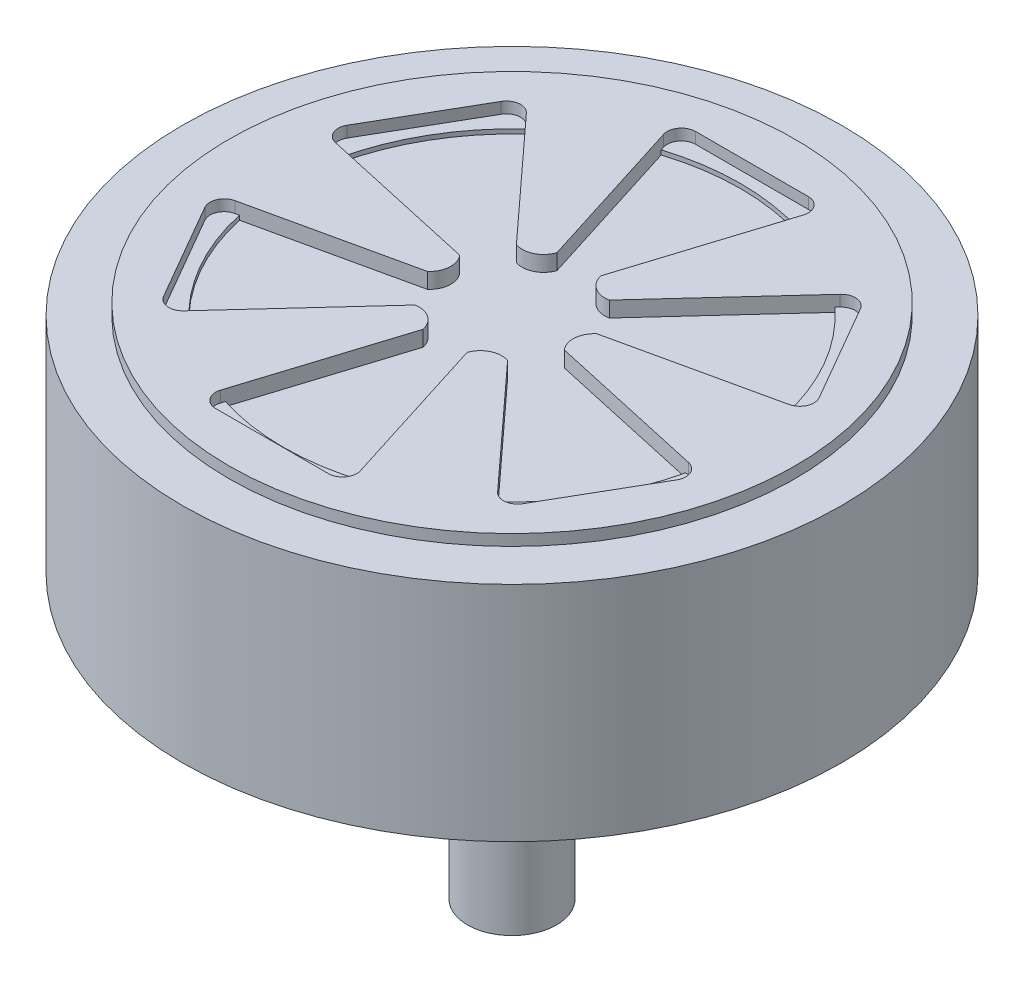
SolidWorks part; units mm, degrees
ref_plane "Front Plane" through (0, 0, 0) normal (0, 0, 1) x (1, 0, 0)
ref_plane "Top Plane" through (0, 0, 0) normal (0, 1, 0) x (1, 0, 0)
ref_plane "Right Plane" through (0, 0, 0) normal (1, 0, 0) x (0, 0, -1)
sketch "Sketch3" plane through (0, 0, 0) normal (0, 1, 0) x (1, 0, 0)
  circle A0 centre (0, 0) radius 59.15
  circle A1 centre (0, 0) radius 38.25
  dimension "D1" = 118.3
extrude "Boss-Extrude1" add sketch "Sketch3" along normal blind 40
sketch "Sketch4" plane through (0, 40, 0) normal (0, 1, 0) x (1, 0, 0)
  circle A0 centre (0, 0) radius 41.021
extrude "Cut-Extrude1" cut sketch "Sketch4" against normal blind 3.556
ref_plane "Plane1" through (0, 20, 0) normal (0, 1, 0) x (1, 0, 0)
mirror "Mirror1" about plane through (0, 20, 0) normal (0, 1, 0) of "Cut-Extrude1"
sketch "Sketch5" plane through (0, 40, 0) normal (0, 1, 0) x (1, 0, 0)
  circle A0 centre (0, 0) radius 59.5177
  circle A1 centre (0, 0) radius 50.8
  dimension "D1" = 101.6
extrude "Boss-Extrude2" add sketch "Sketch5" along normal blind 2 separate body contours A1
sketch "Sketch7" plane through (0, 42, 0) normal (0, 1, 0) x (1, 0, 0)
  circle A0 centre (0, 0) radius 44.45
extrude "Boss-Extrude3" add sketch "Sketch7" against normal blind 7.366 contours A0
sketch "Sketch8" plane through (0, 42, 0) normal (0, 1, 0) x (1, 0, 0)
  line L0 (-3.718, 11.7863) -> (-12.5452, 39.7693)
  line L1 (-10.1229, 43.0734) -> (10.1229, 43.0734)
  line L2 (12.5452, 39.7693) -> (3.8329, 12.1507)
  line L3 (40.7138, 9.0201) -> (12.4393, 2.7559)
  line L4 (8.3482, 9.113) -> (28.1686, 30.7491)
  line L5 (32.2412, 30.3034) -> (42.3641, 12.77)
  line L6 (28.1686, -30.7491) -> (8.6063, -9.3948)
  line L7 (12.0662, -2.6733) -> (40.7138, -9.0201)
  line L8 (42.3641, -12.77) -> (32.2412, -30.3034)
  line L9 (-12.5452, -39.7693) -> (-3.8329, -12.1507)
  line L10 (3.718, -11.7863) -> (12.5452, -39.7693)
  line L11 (10.1229, -43.0734) -> (-10.1229, -43.0734)
  line L12 (-40.7138, -9.0201) -> (-12.4393, -2.7559)
  line L13 (-8.3482, -9.113) -> (-28.1686, -30.7491)
  line L14 (-32.2412, -30.3034) -> (-42.3641, -12.77)
  line L15 (-28.1686, 30.7491) -> (-8.6063, 9.3948)
  line L16 (-12.0662, 2.6733) -> (-40.7138, 9.0201)
  line L17 (-42.3641, 12.77) -> (-32.2412, 30.3034)
  arc A0 (10.1229, 43.0734) -> (12.5452, 39.7693) centre (10.1229, 40.5334) cw
  arc A1 (-12.5452, 39.7693) -> (-10.1229, 43.0734) centre (-10.1229, 40.5334) cw
  arc A2 (42.3641, 12.77) -> (40.7138, 9.0201) centre (40.1644, 11.5) cw
  arc A3 (28.1686, 30.7491) -> (32.2412, 30.3034) centre (30.0415, 29.0334) cw
  arc A4 (32.2412, -30.3034) -> (28.1686, -30.7491) centre (30.0415, -29.0334) cw
  arc A5 (40.7138, -9.0201) -> (42.3641, -12.77) centre (40.1644, -11.5) cw
  arc A6 (-10.1229, -43.0734) -> (-12.5452, -39.7693) centre (-10.1229, -40.5334) cw
  arc A7 (12.5452, -39.7693) -> (10.1229, -43.0734) centre (10.1229, -40.5334) cw
  arc A8 (-42.3641, -12.77) -> (-40.7138, -9.0201) centre (-40.1644, -11.5) cw
  arc A9 (-28.1686, -30.7491) -> (-32.2412, -30.3034) centre (-30.0415, -29.0334) cw
  arc A10 (-32.2412, 30.3034) -> (-28.1686, 30.7491) centre (-30.0415, 29.0334) cw
  arc A11 (-40.7138, 9.0201) -> (-42.3641, 12.77) centre (-40.1644, 11.5) cw
  arc A13 (-8.6063, 9.3948) -> (-3.718, 11.7863) centre (-7.3579, 13.0347) ccw
  arc A14 (3.8329, 12.1507) -> (8.3482, 9.113) centre (7.6094, 12.8895) ccw
  arc A15 (12.4393, 2.7559) -> (12.0662, -2.6733) centre (14.9673, -0.1452) ccw
  arc A16 (8.6063, -9.3948) -> (3.718, -11.7863) centre (7.3579, -13.0347) ccw
  arc A17 (-3.8329, -12.1507) -> (-8.3482, -9.113) centre (-7.6094, -12.8895) ccw
  arc A18 (-12.4393, -2.7559) -> (-12.0662, 2.6733) centre (-14.9673, 0.1452) ccw
  point P59 (0, 0)
  dimension "D1" = 2.54
  dimension "D3" = 6
  dimension "D2" = 6
extrude "Cut-Extrude2" cut sketch "Sketch8" against normal blind 2.794
sketch "Sketch10" plane through (0, 39.206, 0) normal (0, 1, 0) x (1, 0, 0)
  line L36 (10.1229, 45.6134) -> (-10.1229, 45.6134)
  line L37 (-14.9676, 39.0051) -> (-6.4717, 12.0726)
  line L38 (-7.299, 11.728) -> (-26.2957, 32.4649)
  line L39 (-34.4409, 31.5734) -> (-44.5638, 14.04)
  line L40 (-41.2632, 6.5403) -> (-13.691, 0.4317)
  line L41 (-13.8062, -0.4572) -> (-41.2632, -6.5403)
  line L42 (-44.5638, -14.04) -> (-34.4409, -31.5734)
  line L43 (-26.2957, -32.4649) -> (-7.2193, -11.6409)
  line L44 (-6.5072, -12.1851) -> (-14.9676, -39.0051)
  line L45 (-10.1229, -45.6134) -> (10.1229, -45.6134)
  line L46 (14.9676, -39.0051) -> (6.4717, -12.0726)
  line L47 (7.299, -11.728) -> (26.2957, -32.4649)
  line L48 (34.4409, -31.5734) -> (44.5638, -14.04)
  line L49 (41.2632, -6.5403) -> (13.691, -0.4317)
  line L50 (13.8062, 0.4572) -> (41.2632, 6.5403)
  line L51 (44.5638, 14.04) -> (34.4409, 31.5734)
  line L52 (26.2957, 32.4649) -> (7.2193, 11.6409)
  line L53 (6.5072, 12.1851) -> (14.9676, 39.0051)
  line L54 (10.1229, 45.6134) -> (-10.1229, 45.6134)
  line L55 (-14.9676, 39.0051) -> (-6.4717, 12.0726)
  line L56 (-7.299, 11.728) -> (-26.2957, 32.4649)
  line L57 (-34.4409, 31.5734) -> (-44.5638, 14.04)
  line L58 (-41.2632, 6.5403) -> (-13.691, 0.4317)
  line L59 (-13.8062, -0.4572) -> (-41.2632, -6.5403)
  line L60 (-44.5638, -14.04) -> (-34.4409, -31.5734)
  line L61 (-26.2957, -32.4649) -> (-7.2193, -11.6409)
  line L62 (-6.5072, -12.1851) -> (-14.9676, -39.0051)
  line L63 (-10.1229, -45.6134) -> (10.1229, -45.6134)
  line L64 (14.9676, -39.0051) -> (6.4717, -12.0726)
  line L65 (7.299, -11.728) -> (26.2957, -32.4649)
  line L66 (34.4409, -31.5734) -> (44.5638, -14.04)
  line L67 (41.2632, -6.5403) -> (13.691, -0.4317)
  line L68 (13.8062, 0.4572) -> (41.2632, 6.5403)
  line L69 (44.5638, 14.04) -> (34.4409, 31.5734)
  line L70 (26.2957, 32.4649) -> (7.2193, 11.6409)
  line L71 (6.5072, 12.1851) -> (14.9676, 39.0051)
  arc A36 (14.9676, 39.0051) -> (10.1229, 45.6134) centre (10.1229, 40.5334) ccw
  arc A37 (-10.1229, 45.6134) -> (-14.9676, 39.0051) centre (-10.1229, 40.5334) ccw
  arc A38 (-7.299, 11.728) -> (-6.4717, 12.0726) centre (-7.3579, 13.0347) ccw
  arc A39 (-26.2957, 32.4649) -> (-34.4409, 31.5734) centre (-30.0415, 29.0334) ccw
  arc A40 (-44.5638, 14.04) -> (-41.2632, 6.5403) centre (-40.1644, 11.5) ccw
  arc A41 (-13.8062, -0.4572) -> (-13.691, 0.4317) centre (-14.9673, 0.1452) ccw
  arc A42 (-41.2632, -6.5403) -> (-44.5638, -14.04) centre (-40.1644, -11.5) ccw
  arc A43 (-34.4409, -31.5734) -> (-26.2957, -32.4649) centre (-30.0415, -29.0334) ccw
  arc A44 (-6.5072, -12.1851) -> (-7.2193, -11.6409) centre (-7.6094, -12.8895) ccw
  arc A45 (-14.9676, -39.0051) -> (-10.1229, -45.6134) centre (-10.1229, -40.5334) ccw
  arc A46 (10.1229, -45.6134) -> (14.9676, -39.0051) centre (10.1229, -40.5334) ccw
  arc A47 (7.299, -11.728) -> (6.4717, -12.0726) centre (7.3579, -13.0347) ccw
  arc A48 (26.2957, -32.4649) -> (34.4409, -31.5734) centre (30.0415, -29.0334) ccw
  arc A49 (44.5638, -14.04) -> (41.2632, -6.5403) centre (40.1644, -11.5) ccw
  arc A50 (13.8062, 0.4572) -> (13.691, -0.4317) centre (14.9673, -0.1452) ccw
  arc A51 (41.2632, 6.5403) -> (44.5638, 14.04) centre (40.1644, 11.5) ccw
  arc A52 (34.4409, 31.5734) -> (26.2957, 32.4649) centre (30.0415, 29.0334) ccw
  arc A53 (6.5072, 12.1851) -> (7.2193, 11.6409) centre (7.6094, 12.8895) ccw
  arc A54 (14.9676, 39.0051) -> (10.1229, 45.6134) centre (10.1229, 40.5334) ccw
  arc A55 (-10.1229, 45.6134) -> (-14.9676, 39.0051) centre (-10.1229, 40.5334) ccw
  arc A56 (-7.299, 11.728) -> (-6.4717, 12.0726) centre (-7.3579, 13.0347) ccw
  arc A57 (-26.2957, 32.4649) -> (-34.4409, 31.5734) centre (-30.0415, 29.0334) ccw
  arc A58 (-44.5638, 14.04) -> (-41.2632, 6.5403) centre (-40.1644, 11.5) ccw
  arc A59 (-13.8062, -0.4572) -> (-13.691, 0.4317) centre (-14.9673, 0.1452) ccw
  arc A60 (-41.2632, -6.5403) -> (-44.5638, -14.04) centre (-40.1644, -11.5) ccw
  arc A61 (-34.4409, -31.5734) -> (-26.2957, -32.4649) centre (-30.0415, -29.0334) ccw
  arc A62 (-6.5072, -12.1851) -> (-7.2193, -11.6409) centre (-7.6094, -12.8895) ccw
  arc A63 (-14.9676, -39.0051) -> (-10.1229, -45.6134) centre (-10.1229, -40.5334) ccw
  arc A64 (10.1229, -45.6134) -> (14.9676, -39.0051) centre (10.1229, -40.5334) ccw
  arc A65 (7.299, -11.728) -> (6.4717, -12.0726) centre (7.3579, -13.0347) ccw
  arc A66 (26.2957, -32.4649) -> (34.4409, -31.5734) centre (30.0415, -29.0334) ccw
  arc A67 (44.5638, -14.04) -> (41.2632, -6.5403) centre (40.1644, -11.5) ccw
  arc A68 (13.8062, 0.4572) -> (13.691, -0.4317) centre (14.9673, -0.1452) ccw
  arc A69 (41.2632, 6.5403) -> (44.5638, 14.04) centre (40.1644, 11.5) ccw
  arc A70 (34.4409, 31.5734) -> (26.2957, 32.4649) centre (30.0415, 29.0334) ccw
  arc A71 (6.5072, 12.1851) -> (7.2193, 11.6409) centre (7.6094, 12.8895) ccw
  dimension "D1" = 2.54
extrude "Boss-Extrude5" add sketch "Sketch10" against normal blind 13.91
sketch "Sketch11" plane through (0, 3.556, 0) normal (0, -1, 0) x (1, 0, 0)
  circle A0 centre (0, 0) radius 41.021
extrude "Boss-Extrude6" add sketch "Sketch11" along normal blind 4.318
sketch "Sketch12" plane through (0, -0.762, 0) normal (0, -1, 0) x (1, 0, 0)
  circle A0 centre (0, 0) radius 8
  dimension "D1" = 16
extrude "Boss-Extrude7" add sketch "Sketch12" along normal blind 50
